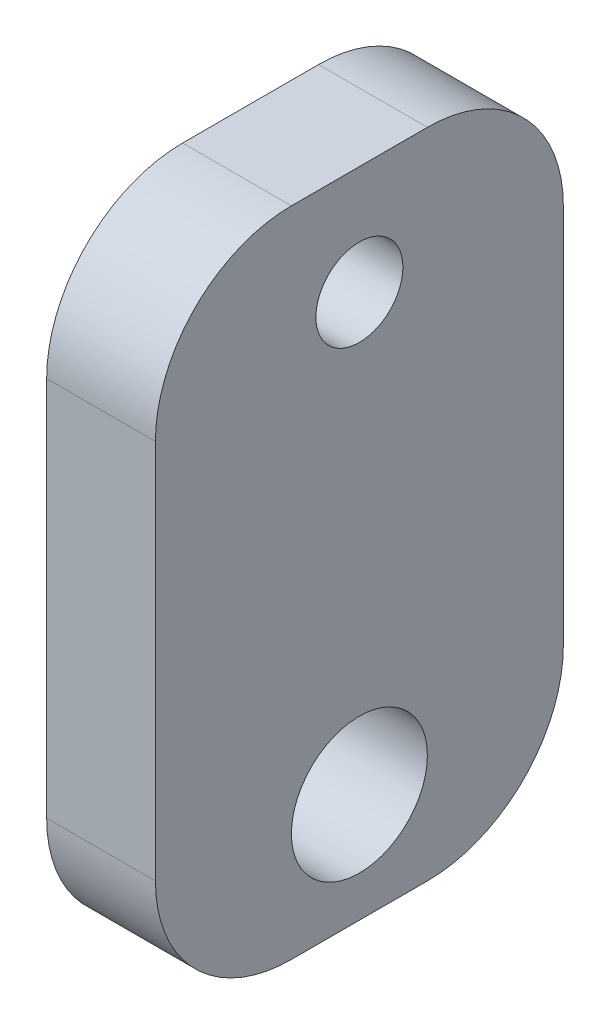
SolidWorks part; units mm, degrees
ref_plane "Front" through (0, 0, 0) normal (0, 0, 1) x (1, 0, 0)
ref_plane "Top" through (0, 0, 0) normal (0, 1, 0) x (1, 0, 0)
ref_plane "Right" through (0, 0, 0) normal (1, 0, 0) x (0, 0, -1)
sketch "Sketch1" plane through (0, 0, 0) normal (1, 0, 0) x (0, 0, -1)
  line L1 (0, 0) -> (15, 0)
  line L2 (0, 0) -> (0, -24)
  line L3 (0, -24) -> (15, -24)
  line L4 (15, 0) -> (15, -24)
  dimension "D1" = 24
  dimension "D2" = 15
extrude "Boss-Extrude1" add sketch "Sketch1" along normal blind 4
sketch "Sketch2" plane through (4, 0, 0) normal (1, 0, 0) x (0, 0, -1)
  line L0 (15, -24) -> (15, 0) construction
  line L1 (15, 0) -> (0, 0) construction
  line L2 (0, -24) -> (15, -24) construction
  circle A0 centre (7.5, -20) radius 2.5
  circle A1 centre (7.5, -4) radius 1.6
  dimension "D1" = 5
  dimension "D2" = 3.2
  dimension "D3" = 7.5
  dimension "D4" = 7.5
  dimension "D5" = 4
  dimension "D6" = 4
extrude "Cut-Extrude1" cut sketch "Sketch2" against normal through all
fillet "Fillet1" radius 5 4 edges at (2, -24, -15) (2, -24, 0) (2, 0, 0) (2, 0, -15)
